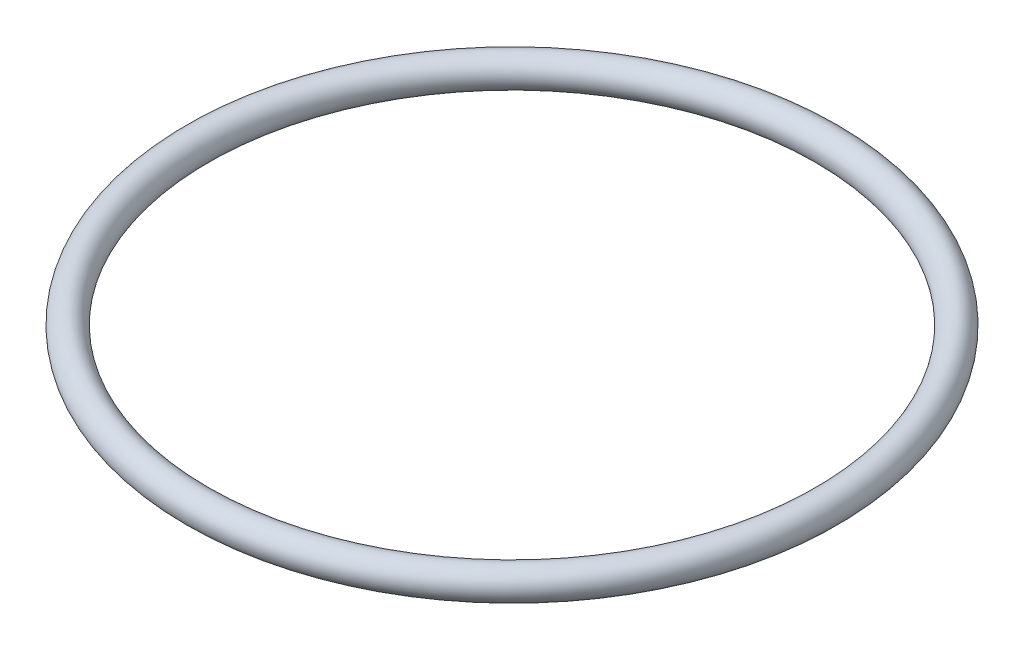
SolidWorks part; units mm, degrees
ref_plane "Front Plane" through (0, 0, 0) normal (0, 0, 1) x (1, 0, 0)
ref_plane "Top Plane" through (0, 0, 0) normal (0, 1, 0) x (1, 0, 0)
ref_plane "Right Plane" through (0, 0, 0) normal (1, 0, 0) x (0, 0, -1)
sketch "Sketch2" plane through (0, 0, 0) normal (0, 0, 1) x (1, 0, 0)
  line L0 (0, 0) -> (0, 22.5506) construction
  circle A0 centre (20.5, 0) radius 1
  dimension "D3" = 2
  dimension "D1" = 22.5506
  dimension "D2" = 20.5
revolve "Revolve1" add sketch "Sketch2" angle 360 about L0
sketch "Sketch3" plane through (0, 0, 0) normal (0, 1, 0) x (1, 0, 0)
  circle A0 centre (0, 0) radius 20.5
  dimension "D1" = 41
